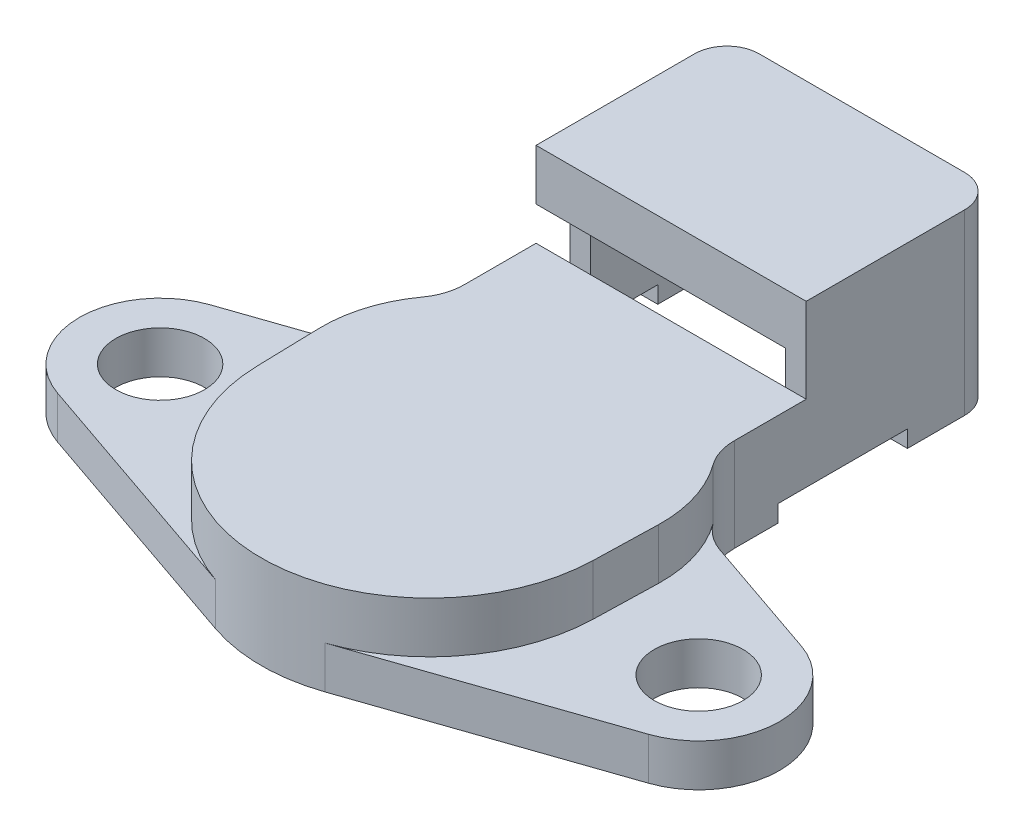
SolidWorks part; units mm, degrees
ref_plane "Front Plane" through (0, 0, 0) normal (0, 0, 1) x (1, 0, 0)
ref_plane "Top Plane" through (0, 0, 0) normal (0, 1, 0) x (1, 0, 0)
ref_plane "Right Plane" through (0, 0, 0) normal (1, 0, 0) x (0, 0, -1)
sketch "Sketch1" plane through (0, 0, 0) normal (0, 1, 0) x (1, 0, 0)
  line L30 (-6.7564, 4.8768) -> (-6.7564, 12.6)
  line L31 (-6.7564, 12.6) -> (-7.9629, 12.6)
  line L32 (-7.9629, 12.6) -> (-7.9629, 10.0193)
  line L33 (-10.1067, 7.0165) -> (-17.4219, 4.5043)
  line L34 (-17.4219, -4.5043) -> (-3.2216, -9.3809)
  line L35 (3.2216, -9.3809) -> (17.4219, -4.5043)
  line L36 (17.4219, 4.5043) -> (10.1067, 7.0165)
  line L37 (7.9629, 10.0193) -> (7.9629, 12.6)
  line L38 (7.9629, 12.6) -> (6.7564, 12.6)
  line L39 (6.7564, 12.6) -> (6.7564, 4.8768)
  line L46 (-6.7564, 20.22) -> (-6.7564, 24.25)
  line L47 (-6.7564, 24.25) -> (6.7564, 24.25)
  line L48 (6.7564, 24.25) -> (6.7564, 20.22)
  line L49 (6.7564, 20.22) -> (7.9629, 20.22)
  line L50 (7.9629, 20.22) -> (7.9629, 25.5)
  line L51 (7.9629, 25.5) -> (-7.9629, 25.5)
  line L52 (-7.9629, 25.5) -> (-7.9629, 20.22)
  line L53 (-7.9629, 20.22) -> (-6.7564, 20.22)
  circle A10 centre (15.875, 0) radius 2.6162
  circle A12 centre (-15.875, 0) radius 2.6162
  arc A28 (-6.7965, 4.8183) -> (-6.7564, 4.8768) centre (-8.6614, 6.1404) ccw
  arc A29 (-10.1067, 7.0165) -> (-7.9629, 10.0193) centre (-11.1379, 10.0193) ccw
  arc A30 (-17.4219, 4.5043) -> (-17.4219, -4.5043) centre (-15.875, 0) ccw
  arc A31 (-3.2216, -9.3809) -> (3.2216, -9.3809) centre (0, 0) ccw
  arc A32 (17.4219, -4.5043) -> (17.4219, 4.5043) centre (15.875, 0) ccw
  arc A33 (7.9629, 10.0193) -> (10.1067, 7.0165) centre (11.1379, 10.0193) ccw
  arc A34 (6.7564, 4.8768) -> (6.7965, 4.8183) centre (8.6614, 6.1404) ccw
  arc A35 (-6.7965, 4.8183) -> (6.7965, 4.8183) centre (0, 0) ccw
sketch "Sketch3" plane through (0, 0, 0) normal (0, 1, 0) x (1, 0, 0)
  line L0 (6.7564, 24.25) -> (6.7564, 20.22) construction
  line L1 (6.7564, 20.22) -> (7.9629, 20.22) construction
  line L2 (7.9629, 20.22) -> (7.9629, 25.5) construction
  line L3 (7.9629, 25.5) -> (-7.9629, 25.5) construction
  line L4 (-7.9629, 25.5) -> (-7.9629, 20.22) construction
  line L5 (-7.9629, 20.22) -> (-6.7564, 20.22) construction
  line L6 (-6.7564, 20.22) -> (-6.7564, 24.25) construction
  line L7 (-6.7564, 24.25) -> (6.7564, 24.25) construction
  line L8 (6.7564, 12.6) -> (6.7564, 4.8768) construction
  line L9 (7.9629, 12.6) -> (6.7564, 12.6) construction
  line L10 (7.9629, 10.0193) -> (7.9629, 12.6) construction
  line L11 (17.4219, 4.5043) -> (10.1067, 7.0165) construction
  line L12 (3.2216, -9.3809) -> (17.4219, -4.5043) construction
  line L13 (-17.4219, -4.5043) -> (-3.2216, -9.3809) construction
  line L14 (-10.1067, 7.0165) -> (-17.4219, 4.5043) construction
  line L15 (-7.9629, 12.6) -> (-7.9629, 10.0193) construction
  line L16 (-6.7564, 12.6) -> (-7.9629, 12.6) construction
  line L17 (-6.7564, 4.8768) -> (-6.7564, 12.6) construction
  line L18 (6.7564, 24.25) -> (6.7564, 20.22)
  line L19 (6.7564, 20.22) -> (7.9629, 20.22)
  line L20 (7.9629, 20.22) -> (7.9629, 25.5)
  line L21 (7.9629, 25.5) -> (-7.9629, 25.5)
  line L22 (-7.9629, 25.5) -> (-7.9629, 20.22)
  line L23 (-7.9629, 20.22) -> (-6.7564, 20.22)
  line L24 (-6.7564, 20.22) -> (-6.7564, 24.25)
  line L25 (-6.7564, 24.25) -> (6.7564, 24.25)
  line L26 (6.7564, 12.6) -> (6.7564, 4.8768)
  line L27 (7.9629, 12.6) -> (6.7564, 12.6)
  line L28 (7.9629, 10.0193) -> (7.9629, 12.6)
  line L29 (17.4219, 4.5043) -> (10.1067, 7.0165)
  line L30 (3.2216, -9.3809) -> (17.4219, -4.5043)
  line L31 (-17.4219, -4.5043) -> (-3.2216, -9.3809)
  line L32 (-10.1067, 7.0165) -> (-17.4219, 4.5043)
  line L33 (-7.9629, 12.6) -> (-7.9629, 10.0193)
  line L34 (-6.7564, 12.6) -> (-7.9629, 12.6)
  line L35 (-6.7564, 4.8768) -> (-6.7564, 12.6)
  circle A0 centre (-15.875, 0) radius 2.6162 construction
  circle A1 centre (15.875, 0) radius 2.6162 construction
  arc A2 (-6.7965, 4.8183) -> (6.7965, 4.8183) centre (0, 0) ccw construction
  arc A3 (6.7564, 4.8768) -> (6.7965, 4.8183) centre (8.6614, 6.1404) ccw construction
  arc A4 (7.9629, 10.0193) -> (10.1067, 7.0165) centre (11.1379, 10.0193) ccw construction
  arc A5 (17.4219, -4.5043) -> (17.4219, 4.5043) centre (15.875, 0) ccw construction
  arc A6 (-3.2216, -9.3809) -> (3.2216, -9.3809) centre (0, 0) ccw construction
  arc A7 (-17.4219, 4.5043) -> (-17.4219, -4.5043) centre (-15.875, 0) ccw construction
  arc A8 (-10.1067, 7.0165) -> (-7.9629, 10.0193) centre (-11.1379, 10.0193) ccw construction
  arc A9 (-6.7965, 4.8183) -> (-6.7564, 4.8768) centre (-8.6614, 6.1404) ccw construction
  circle A10 centre (-15.875, 0) radius 2.6162
  circle A11 centre (15.875, 0) radius 2.6162
  arc A12 (-6.7965, 4.8183) -> (6.7965, 4.8183) centre (0, 0) ccw
  arc A13 (6.7564, 4.8768) -> (6.7965, 4.8183) centre (8.6614, 6.1404) ccw
  arc A14 (7.9629, 10.0193) -> (10.1067, 7.0165) centre (11.1379, 10.0193) ccw
  arc A15 (17.4219, -4.5043) -> (17.4219, 4.5043) centre (15.875, 0) ccw
  arc A16 (-3.2216, -9.3809) -> (3.2216, -9.3809) centre (0, 0) ccw
  arc A17 (-17.4219, 4.5043) -> (-17.4219, -4.5043) centre (-15.875, 0) ccw
  arc A18 (-10.1067, 7.0165) -> (-7.9629, 10.0193) centre (-11.1379, 10.0193) ccw
  arc A19 (-6.7965, 4.8183) -> (-6.7564, 4.8768) centre (-8.6614, 6.1404) ccw
extrude "Boss-Extrude1" add sketch "Sketch3" along normal blind 1
sketch "Sketch4" plane through (0, 1, 0) normal (0, 1, 0) x (1, 0, 0)
  line L0 (-6.7564, 24.25) -> (6.7564, 24.25) construction
  line L1 (6.7564, 24.25) -> (6.7564, 20.22) construction
  line L3 (7.9629, 20.22) -> (7.9629, 25.5) construction
  line L4 (7.9629, 25.5) -> (-7.9629, 25.5) construction
  line L5 (-7.9629, 25.5) -> (-7.9629, 20.22) construction
  line L7 (-6.7564, 20.22) -> (-6.7564, 24.25) construction
  line L8 (-6.7564, 4.8768) -> (-6.7564, 12.6) construction
  line L10 (-7.9629, 12.6) -> (-7.9629, 10.0193) construction
  line L11 (-10.1067, 7.0165) -> (-17.4219, 4.5043) construction
  line L12 (-17.4219, -4.5043) -> (-3.2216, -9.3809) construction
  line L13 (3.2216, -9.3809) -> (17.4219, -4.5043) construction
  line L14 (17.4219, 4.5043) -> (10.1067, 7.0165) construction
  line L15 (7.9629, 10.0193) -> (7.9629, 12.6) construction
  line L17 (6.7564, 12.6) -> (6.7564, 4.8768) construction
  line L18 (-6.7564, 24.25) -> (6.7564, 24.25)
  line L19 (6.7564, 24.25) -> (6.7564, 20.22)
  line L21 (7.9629, 20.22) -> (7.9629, 25.5)
  line L22 (7.9629, 25.5) -> (-7.9629, 25.5)
  line L23 (-7.9629, 25.5) -> (-7.9629, 20.22)
  line L25 (-6.7564, 20.22) -> (-6.7564, 24.25)
  line L26 (-6.7564, 4.8768) -> (-6.7564, 12.6)
  line L28 (-7.9629, 12.6) -> (-7.9629, 10.0193)
  line L29 (-10.1067, 7.0165) -> (-17.4219, 4.5043)
  line L30 (-17.4219, -4.5043) -> (-3.2216, -9.3809)
  line L31 (3.2216, -9.3809) -> (17.4219, -4.5043)
  line L32 (17.4219, 4.5043) -> (10.1067, 7.0165)
  line L33 (7.9629, 10.0193) -> (7.9629, 12.6)
  line L35 (6.7564, 12.6) -> (6.7564, 4.8768)
  line L36 (7.9629, 12.6) -> (7.9629, 20.22)
  line L37 (6.7564, 20.22) -> (6.7564, 12.6)
  line L38 (-6.7564, 20.22) -> (-6.7564, 12.6)
  line L39 (-7.9629, 20.22) -> (-7.9629, 12.6)
  arc A0 (-6.7965, 4.8183) -> (-6.7564, 4.8768) centre (-8.6614, 6.1404) ccw construction
  circle A1 centre (15.875, 0) radius 2.6162
  circle A2 centre (15.875, 0) radius 2.6162
  circle A3 centre (-15.875, 0) radius 2.6162
  circle A4 centre (-15.875, 0) radius 2.6162
  arc A5 (-10.1067, 7.0165) -> (-7.9629, 10.0193) centre (-11.1379, 10.0193) ccw construction
  arc A6 (-17.4219, 4.5043) -> (-17.4219, -4.5043) centre (-15.875, 0) ccw construction
  arc A7 (-3.2216, -9.3809) -> (3.2216, -9.3809) centre (0, 0) ccw construction
  arc A8 (17.4219, -4.5043) -> (17.4219, 4.5043) centre (15.875, 0) ccw construction
  arc A9 (7.9629, 10.0193) -> (10.1067, 7.0165) centre (11.1379, 10.0193) ccw construction
  arc A10 (6.7564, 4.8768) -> (6.7965, 4.8183) centre (8.6614, 6.1404) ccw construction
  arc A11 (-6.7965, 4.8183) -> (6.7965, 4.8183) centre (0, 0) ccw construction
  arc A12 (-6.7965, 4.8183) -> (-6.7564, 4.8768) centre (-8.6614, 6.1404) ccw
  arc A13 (-10.1067, 7.0165) -> (-7.9629, 10.0193) centre (-11.1379, 10.0193) ccw
  arc A14 (-17.4219, 4.5043) -> (-17.4219, -4.5043) centre (-15.875, 0) ccw
  arc A15 (-3.2216, -9.3809) -> (3.2216, -9.3809) centre (0, 0) ccw
  arc A16 (17.4219, -4.5043) -> (17.4219, 4.5043) centre (15.875, 0) ccw
  arc A17 (7.9629, 10.0193) -> (10.1067, 7.0165) centre (11.1379, 10.0193) ccw
  arc A18 (6.7564, 4.8768) -> (6.7965, 4.8183) centre (8.6614, 6.1404) ccw
  arc A19 (-6.7965, 4.8183) -> (6.7965, 4.8183) centre (0, 0) ccw
  dimension "D1" = 0
  dimension "D2" = 0
extrude "Boss-Extrude2" add sketch "Sketch4" along normal blind 1.5
sketch "Sketch5" plane through (0, 2.5, 0) normal (0, 1, 0) x (1, 0, 0)
  line L0 (-9.9153, -0.2608) -> (-10.1067, 7.0165)
  line L1 (10.1067, 7.0165) -> (9.9153, -0.2608)
  line L3 (-6.7564, 24.25) -> (-6.7564, 4.8768)
  line L4 (6.7564, 24.25) -> (-6.7564, 24.25)
  line L5 (6.7564, 4.8768) -> (6.7564, 24.25)
  line L6 (-6.7564, 24.25) -> (-6.7564, 4.8768)
  line L7 (6.7564, 24.25) -> (-6.7564, 24.25)
  line L8 (6.7564, 4.8768) -> (6.7564, 24.25)
  line L15 (7.9629, 10.0193) -> (7.9629, 25.5)
  line L16 (7.9629, 25.5) -> (-7.9629, 25.5)
  line L17 (-7.9629, 25.5) -> (-7.9629, 10.0193)
  line L18 (-10.1067, 7.0165) -> (-17.4219, 4.5043)
  line L19 (-17.4219, -4.5043) -> (-3.2216, -9.3809)
  line L20 (3.2216, -9.3809) -> (17.4219, -4.5043)
  line L21 (17.4219, 4.5043) -> (10.1067, 7.0165)
  line L22 (7.9629, 10.0193) -> (7.9629, 25.5)
  line L23 (7.9629, 25.5) -> (-7.9629, 25.5)
  line L24 (-7.9629, 25.5) -> (-7.9629, 10.0193)
  line L25 (-10.1067, 7.0165) -> (-17.4219, 4.5043)
  line L26 (-17.4219, -4.5043) -> (-3.2216, -9.3809)
  line L27 (3.2216, -9.3809) -> (17.4219, -4.5043)
  line L28 (17.4219, 4.5043) -> (10.1067, 7.0165)
  arc A0 (-9.9153, -0.2608) -> (9.9153, -0.2608) centre (0, 0) ccw
  circle A1 centre (15.875, 0) radius 2.6162
  circle A2 centre (15.875, 0) radius 2.6162 construction
  arc A3 (-6.7965, 4.8183) -> (-6.7564, 4.8768) centre (-8.6614, 6.1404) ccw
  arc A4 (6.7564, 4.8768) -> (6.7965, 4.8183) centre (8.6614, 6.1404) ccw
  arc A5 (-6.7965, 4.8183) -> (6.7965, 4.8183) centre (0, 0) ccw
  arc A6 (-6.7965, 4.8183) -> (-6.7564, 4.8768) centre (-8.6614, 6.1404) ccw
  arc A7 (6.7564, 4.8768) -> (6.7965, 4.8183) centre (8.6614, 6.1404) ccw
  circle A9 centre (-15.875, 0) radius 2.6162
  circle A10 centre (-15.875, 0) radius 2.6162 construction
  arc A11 (-3.2216, -9.3809) -> (3.2216, -9.3809) centre (0, 0) ccw construction
  arc A17 (-10.1067, 7.0165) -> (-7.9629, 10.0193) centre (-11.1379, 10.0193) ccw
  arc A18 (-17.4219, 4.5043) -> (-17.4219, -4.5043) centre (-15.875, 0) ccw
  arc A19 (-3.2216, -9.3809) -> (3.2216, -9.3809) centre (0, 0) ccw
  arc A20 (17.4219, -4.5043) -> (17.4219, 4.5043) centre (15.875, 0) ccw
  arc A21 (7.9629, 10.0193) -> (10.1067, 7.0165) centre (11.1379, 10.0193) ccw
  arc A22 (-10.1067, 7.0165) -> (-7.9629, 10.0193) centre (-11.1379, 10.0193) ccw
  arc A23 (-17.4219, 4.5043) -> (-17.4219, -4.5043) centre (-15.875, 0) ccw
  arc A24 (-3.2216, -9.3809) -> (3.2216, -9.3809) centre (0, 0) ccw
  arc A25 (17.4219, -4.5043) -> (17.4219, 4.5043) centre (15.875, 0) ccw
  arc A26 (7.9629, 10.0193) -> (10.1067, 7.0165) centre (11.1379, 10.0193) ccw
  point P22 (0, 0)
  point P23 (0, 0)
  line M24 (7.9629, 10.0193) -> (7.9629, 25.5)
  line M25 (7.9629, 25.5) -> (-7.9629, 25.5)
  line M26 (-7.9629, 25.5) -> (-7.9629, 10.0193)
  arc M27 (-7.9629, 10.0193) -> (-10.1067, 7.0165) centre (-11.1379, 10.0193) cw
  arc M31 (-3.2216, -9.3809) -> (3.2216, -9.3809) centre (0, 0) ccw
  arc M35 (10.1067, 7.0165) -> (7.9629, 10.0193) centre (11.1379, 10.0193) cw
  arc M36 (-6.7965, 4.8183) -> (-6.7564, 4.8768) centre (-8.6614, 6.1404) ccw
  line M37 (-6.7564, 4.8768) -> (-6.7564, 24.25)
  line M38 (-6.7564, 24.25) -> (6.7564, 24.25)
  line M39 (6.7564, 24.25) -> (6.7564, 4.8768)
  arc M40 (6.7564, 4.8768) -> (6.7965, 4.8183) centre (8.6614, 6.1404) ccw
  arc M41 (6.7965, 4.8183) -> (-6.7965, 4.8183) centre (0, 0) cw
  dimension "D1" = 0
  dimension "D2" = 0
  dimension "D3" = 0
  dimension "D4" = 0
extrude "Boss-Extrude3" add sketch "Sketch5" along normal blind 3 contours A0 L1 L0 M31 M35 M24 M25 M26 M27 M41 M36 M37 M38 M39 M40 | M36 M41 M40 M39 M38 M37
sketch "Sketch6" plane through (0, 5.5, 0) normal (0, 1, 0) x (1, 0, 0)
  line L0 (-7.9629, 25.5) -> (-7.9629, 10.0193) construction
  line L1 (7.9629, 25.5) -> (-7.9629, 25.5)
  line L2 (7.9629, 25.5) -> (7.9629, 14.25)
  line L3 (7.9629, 14.25) -> (-7.9629, 14.25)
  line L4 (-7.9629, 25.5) -> (-7.9629, 14.25)
  dimension "D1" = 11.25
extrude "Boss-Extrude4" add sketch "Sketch6" along normal blind 5
sketch "Sketch7" plane through (0, 2.5, 0) normal (0, -1, 0) x (1, 0, 0)
  line L0 (-6.7564, -24.25) -> (-6.7564, -4.8768) construction
  line L1 (6.7564, -24.25) -> (-6.7564, -24.25)
  line L2 (6.7564, -24.25) -> (6.7564, -14.25)
  line L3 (6.7564, -14.25) -> (-6.7564, -14.25)
  line L4 (-6.7564, -24.25) -> (-6.7564, -14.25)
  dimension "D1" = 10
extrude "Cut-Extrude1" cut sketch "Sketch7" against normal blind 5
sketch "Sketch8" plane through (-7.9629, 0, 0) normal (-1, 0, 0) x (0, 0, 1)
  line L0 (-20.22, 1) -> (-12.6, 1) construction
  line L1 (-16.25, 1) -> (-14.25, 1)
  line L2 (-16.25, 1) -> (-16.25, 7.5)
  line L3 (-16.25, 7.5) -> (-14.25, 7.5)
  line L4 (-14.25, 1) -> (-14.25, 7.5)
  line L6 (-14.25, 7.5) -> (-14.25, 5.5) construction
  line L7 (-14.25, 7.5) -> (-14.25, 5.5)
  point P10 (-14.25, 7.4256)
  line M4 (-20.22, 1) -> (-12.6, 1)
  line M9 (-14.25, 5.5) -> (-14.25, 10.5)
  dimension "D1" = 2
extrude "Cut-Extrude2" cut sketch "Sketch8" against normal blind 5 contours L4 L3 L2 M4 M9
fillet "Fillet1" radius 2.54 1 edges at (-6.7564, 1.25, -4.8768)
fillet "Fillet2" radius 2.54 1 edges at (6.7564, 1.25, -4.8768)
fillet "Fillet3" radius 7.62 2 edges at (10.1067, 4, -7.0165) (-10.1067, 4, -7.0165)
fillet "Fillet4" radius 1.905 2 edges at (-7.9629, 5.25, -25.5) (7.9629, 5.25, -25.5)
